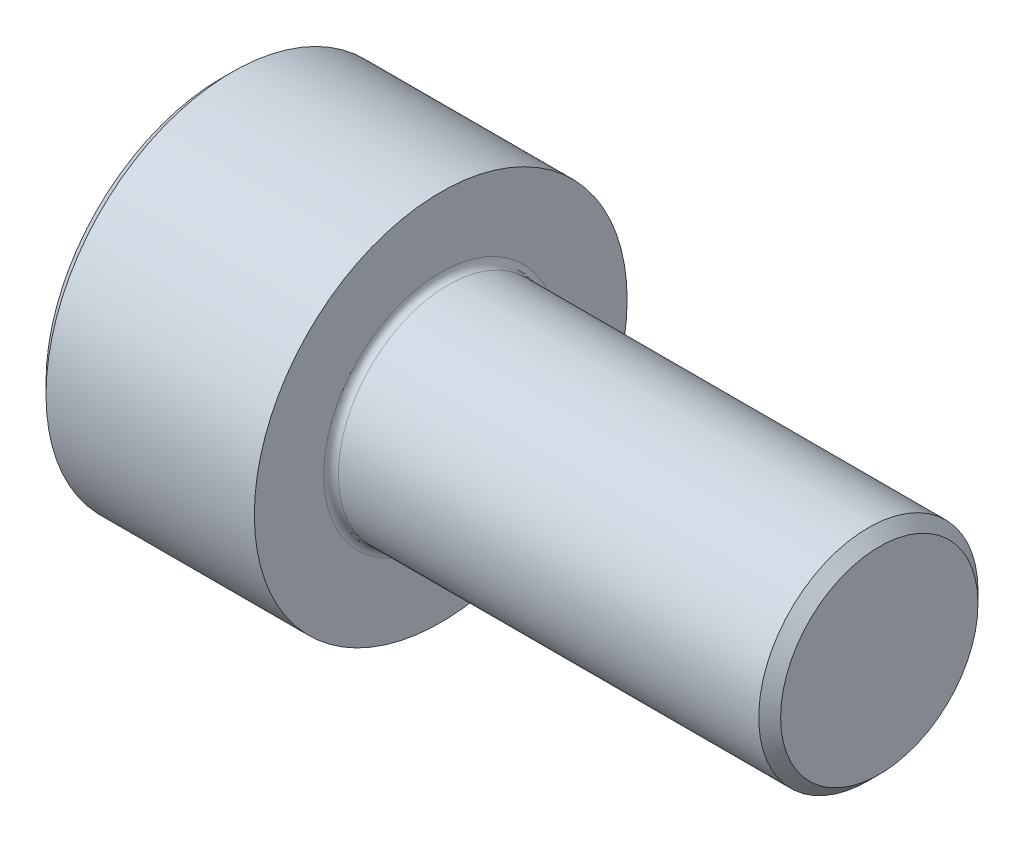
SolidWorks part; units mm, degrees
material "Galvanized Steel"
ref_plane "Plano frontal" through (0, 0, 0) normal (0, 0, 1) x (1, 0, 0)
ref_plane "Plano superior" through (0, 0, 0) normal (0, 1, 0) x (1, 0, 0)
ref_plane "Plano direito" through (0, 0, 0) normal (1, 0, 0) x (0, 0, -1)
ref_plane "Plano1" through (0, 0, 0) normal (0, 0, -1) x (-1, 0, 0)
sketch "Esboço1" plane through (0, 0, 0) normal (0, 0, -1) x (-1, 0, 0)
  line L0 (-6, 5.1) -> (-6, 0)
  line L1 (-6, 0) -> (0, 0)
  line L2 (0, 0) -> (0, 5.1)
  line L3 (0, 5.1) -> (-6, 5.1)
  line L4 (-6, 0) -> (0, 0) construction
  dimension "D1" = 6
  dimension "D2" = 5.1
revolve "Revolução1" add sketch "Esboço1" angle 360 about L4
sketch "Esboço2" plane through (6, 0, 0) normal (1, 0, 0) x (0, 0, -1)
  circle A0 centre (0, 0) radius 3
  dimension "D1" = 6
extrude "Ressalto-extrusão1" add sketch "Esboço2" along normal blind 12
sketch "Esboço3" plane through (0, 0, 0) normal (-1, 0, 0) x (0, 0, 1)
  line L7 (0, 2.9445) -> (-2.55, 1.4722)
  line L8 (-2.55, 1.4722) -> (-2.55, -1.4722)
  line L9 (-2.55, -1.4722) -> (0, -2.9445)
  line L10 (0, -2.9445) -> (2.55, -1.4722)
  line L11 (2.55, -1.4722) -> (2.55, 1.4722)
  line L12 (2.55, 1.4722) -> (0, 2.9445)
  circle A0 centre (0, 0) radius 2.55 construction
  dimension "D1" = 5.1
extrude "Corte-extrusão1" cut sketch "Esboço3" against normal blind 2.5
sketch "Esboço4" plane through (0, 0, 0) normal (0, 0, 1) x (1, 0, 0)
  line L0 (2.5, 2.55) -> (2.5, 0)
  line L1 (2.5, 0) -> (3.9722, 0)
  line L2 (3.9722, 0) -> (2.5, 2.55)
  line L3 (2.5, 0) -> (3.9722, 0) construction
  line L4 (2.5, -1.4722) -> (2.5, 1.4722) construction
  dimension "D1" = 30
  dimension "D2" = 2.55
revolve "Corte-Revolução1" cut sketch "Esboço4" angle 360 about L3
chamfer "Chanfro1" distance 0.3 angle 45 2 edges at (18, 0, -3) (0, 0, 5.1)
fillet "Filete1" radius 0.2 1 edges at (6, 0, -3)
sketch "Sketch1" plane through (0, 0, 0) normal (0, 1, 0) x (1, 0, 0)
  line L0 (0, 2.945) -> (1.7003, 0)
  line L1 (0, 4.8) -> (0, -4.8) construction
  line L2 (2.5, 0) -> (0, 0) construction
  line L3 (1.7003, 0) -> (0, 0)
  line L4 (0, 0) -> (0, 2.945)
  line L5 (1.7003, 0) -> (3.9722, 0) construction
  line L6 (2.5, -2.55) -> (3.9722, 0) construction
  line L7 (3.9722, 0) -> (2.5, 2.55) construction
  dimension "D1" = 5.89
revolve "Cut-Revolve1" cut sketch "Sketch1" angle 360 about L5
